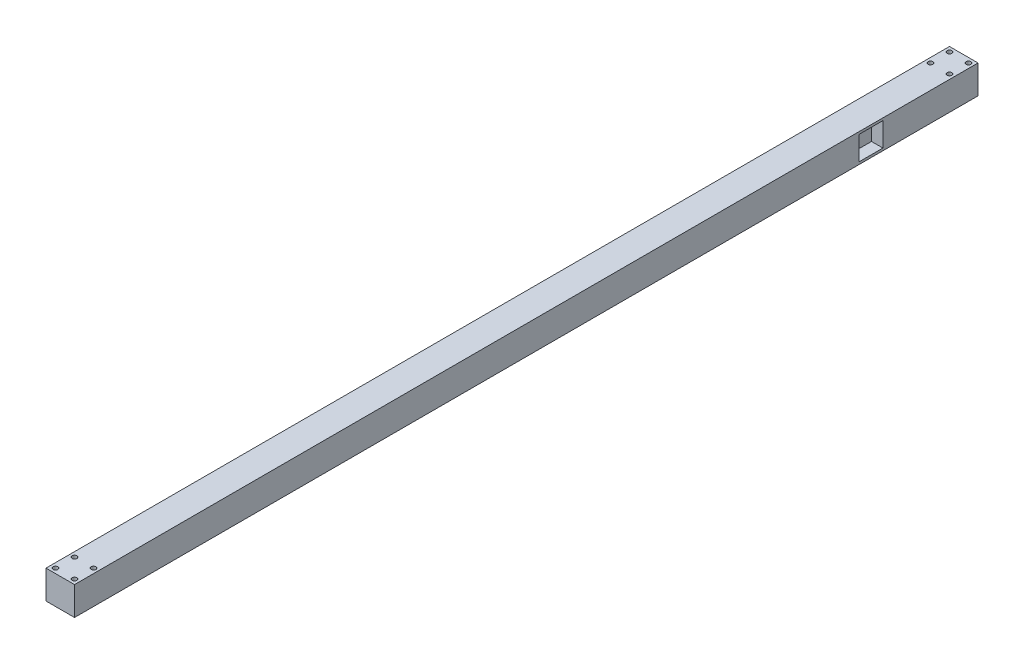
SolidWorks part; units mm, degrees
ref_plane "Front Plane" through (0, 0, 0) normal (0, 0, 1) x (1, 0, 0)
ref_plane "Top Plane" through (0, 0, 0) normal (0, 1, 0) x (1, 0, 0)
ref_plane "Right Plane" through (0, 0, 0) normal (1, 0, 0) x (0, 0, -1)
sketch "Sketch1" plane through (0, 0, 0) normal (0, 0, 1) x (1, 0, 0)
  line L1 (-15, 15) -> (15, 15)
  line L2 (-15, 15) -> (-15, -15)
  line L3 (-15, -15) -> (15, -15)
  line L4 (15, 15) -> (15, -15)
  line L5 (-15, 15) -> (15, -15) construction
  line L6 (-15, -15) -> (15, 15) construction
  point P0 (0, 0)
  dimension "D1" = 30
  dimension "D2" = 30
extrude "Boss-Extrude1" add sketch "Sketch1" along normal blind 950
sketch "Sketch2" plane through (0, 15, 0) normal (0, 1, 0) x (1, 0, 0)
  line L0 (-15, -920) -> (15, -920) construction
  line L1 (15, -950) -> (-15, -950) construction
  line L2 (-15, -30) -> (15, -30) construction
  line L3 (-15, -950) -> (-15, 0) construction
  line L4 (15, -950) -> (15, 0) construction
  line L5 (15, 0) -> (-15, 0) construction
  circle A0 centre (-10, -925) radius 2.5
  circle A1 centre (10, -925) radius 2.5
  circle A2 centre (10, -945) radius 2.5
  circle A3 centre (-10, -945) radius 2.5
  circle A4 centre (-10, -5) radius 2.5
  circle A5 centre (10, -5) radius 2.5
  circle A6 centre (10, -25) radius 2.5
  circle A7 centre (-10, -25) radius 2.5
  dimension "D2" = 5
  dimension "D3" = 5
  dimension "D4" = 5
  dimension "D5" = 5
  dimension "D6" = 5
  dimension "D8" = 5
  dimension "D9" = 5
  dimension "D10" = 5
  dimension "D11" = 5
  dimension "D12" = 5
  dimension "D13" = 5
  dimension "D15" = 5
  dimension "D16" = 5
  dimension "D17" = 5
  dimension "D18" = 5
  dimension "D19" = 5
  dimension "D20" = 5
  dimension "D21" = 5
  dimension "D22" = 5
  dimension "D23" = 5
  dimension "D24" = 5
  dimension "D25" = 5
  dimension "D1" = 30
  dimension "D7" = 5
  dimension "D14" = 30
  dimension "D26" = 5
extrude "Cut-Extrude1" cut sketch "Sketch2" against normal blind 30
sketch "Sketch4" plane through (15, 0, 0) normal (1, 0, 0) x (0, 0, -1)
  line L0 (-950, 15) -> (0, 15) construction
  line L1 (-125, 12.5) -> (-100, 12.5)
  line L2 (-125, 12.5) -> (-125, -12.5)
  line L3 (-125, -12.5) -> (-100, -12.5)
  line L4 (-100, 12.5) -> (-100, -12.5)
  line L5 (-125, 12.5) -> (-100, -12.5) construction
  line L6 (-125, -12.5) -> (-100, 12.5) construction
  line L7 (0, -15) -> (0, 15) construction
  point P0 (-112.5, 0)
  dimension "D1" = 25
  dimension "D2" = 25
  dimension "D3" = 2.5
  dimension "D4" = 100
extrude "Cut-Extrude3" cut sketch "Sketch4" against normal blind 12
